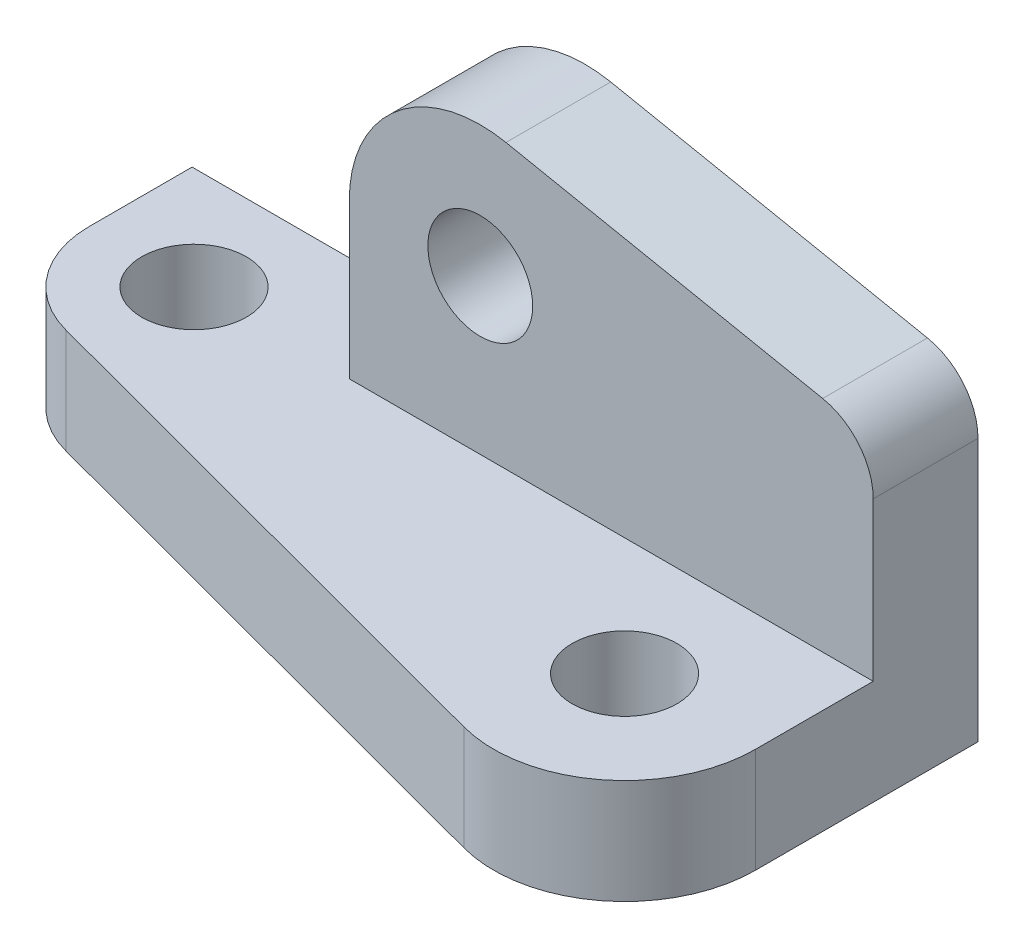
SolidWorks part; units mm, degrees
ref_plane "前基準面" through (0, 0, 0) normal (0, 0, 1) x (1, 0, 0)
ref_plane "上基準面" through (0, 0, 0) normal (0, 1, 0) x (1, 0, 0)
ref_plane "右基準面" through (0, 0, 0) normal (1, 0, 0) x (0, 0, -1)
sketch "草圖1" plane through (0, 0, 0) normal (0, 1, 0) x (1, 0, 0)
  line L0 (0, 0) -> (150, 0)
  line L1 (150, 0) -> (150, -75)
  line L2 (150, -75) -> (0, -35)
  line L3 (0, -35) -> (0, 0)
  dimension "D1" = 35
  dimension "D2" = 75
  dimension "D3" = 150
extrude "填料-伸長1" add sketch "草圖1" along normal blind 20
sketch "草圖2" plane through (0, 0, 0) normal (0, 0, -1) x (-1, 0, 0)
  line L0 (-150, 0) -> (-150, 60)
  line L1 (-150, 60) -> (-50, 80)
  line L2 (-50, 80) -> (-50, 0)
  line L3 (-150, 0) -> (0, 0) construction
  line L4 (-50, 0) -> (-150, 0)
  dimension "D1" = 80
  dimension "D2" = 60
  dimension "D3" = 100
extrude "填料-伸長2" add sketch "草圖2" against normal blind 20
fillet "圓角1" radius 12 1 edges at (150, 60, 10)
fillet "圓角2" radius 20 1 edges at (0, 10, 35)
fillet "圓角3" radius 25 2 edges at (50, 80, 10) (150, 10, 75)
hole_wizard "Ø20.0 (20) 直徑孔1" positions "草圖3" profile "草圖4" hole size "Ø20.0" standard "ISO" end condition through all
sketch "草圖3" plane through (0, 20, 0) normal (0, 1, 0) x (1, 0, 0)
  point P0 (125, -42.4597)
  point P3 (20, -19.6344)
sketch "草圖4" plane through (125, 20, 42.4597) normal (1, 0, 0) x (0, 0, 1)
  line L0 (0, 0) -> (0, 20)
  line L1 (0, 20) -> (10, 20)
  line L2 (10, 20) -> (10, 0)
  line L5 (10, 0) -> (0, 0)
  line L11 (0, -6.35) -> (0, 107.95) construction
  dimension "貫穿孔直徑" = 20
  dimension "貫穿孔深度" = 20
hole_wizard "Ø20.0 (20) 直徑孔2" positions "草圖5" profile "草圖6" hole size "Ø20.0" standard "ISO" end condition through all
sketch "草圖5" plane through (0, 0, 20) normal (0, 0, 1) x (1, 0, 0)
  point P0 (75, 49.5049)
sketch "草圖6" plane through (75, 49.5049, 20) normal (1, 0, 0) x (0, -1, 0)
  line L0 (0, 0) -> (0, 20)
  line L1 (0, 20) -> (10, 20)
  line L2 (10, 20) -> (10, 0)
  line L5 (10, 0) -> (0, 0)
  line L11 (0, -6.35) -> (0, 107.95) construction
  dimension "貫穿孔直徑" = 20
  dimension "貫穿孔深度" = 20
